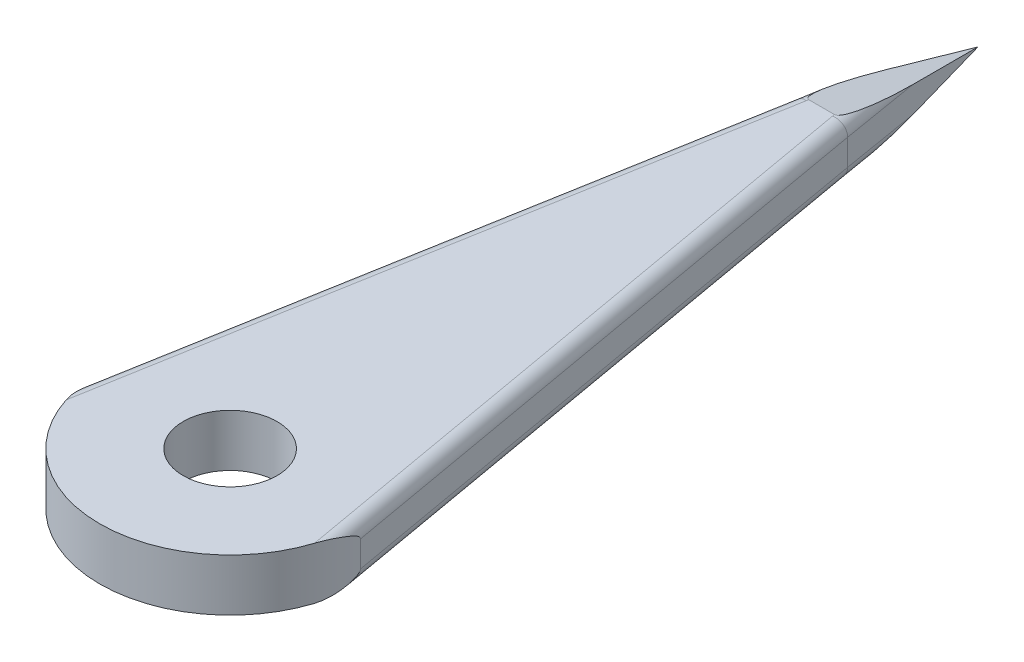
SolidWorks part; units mm, degrees
ref_plane "Front Plane" through (0, 0, 0) normal (0, 0, 1) x (1, 0, 0)
ref_plane "Top Plane" through (0, 0, 0) normal (0, 1, 0) x (1, 0, 0)
ref_plane "Right Plane" through (0, 0, 0) normal (1, 0, 0) x (0, 0, -1)
sketch "Sketch1" plane through (0, 0, 0) normal (0, 1, 0) x (1, 0, 0)
  line L2 (-25, 0) -> (25, 0) construction
  line L3 (25, 0) -> (5, 113.4256)
  line L4 (5, 113.4256) -> (-5, 113.4256)
  line L5 (-5, 113.4256) -> (-25, 0)
  circle A0 centre (0, 0) radius 9
  arc A1 (-25, 0) -> (25, 0) centre (0, 0) ccw
  point P6 (0, 113.4256)
  point P8 (0, -25)
  dimension "D1" = 18
  dimension "D2" = 25
  dimension "D3" = 25
  dimension "D4" = 10
  dimension "D5" = 80
extrude "Boss-Extrude1" add sketch "Sketch1" along normal blind 10
ref_plane "Plane1" through (0, 0, -143.4256) normal (0, 0, -1) x (-1, 0, 0)
sketch "Sketch3" plane through (0, 0, -143.4256) normal (0, 0, -1) x (-1, 0, 0)
  point P0 (0, 5)
sketch "Sketch4" plane through (0, 0, -113.4256) normal (0, 0, -1) x (-1, 0, 0)
  line L1 (-5, 10) -> (5, 10)
  line L2 (-5, 10) -> (-5, 0)
  line L3 (-5, 0) -> (5, 0)
  line L4 (5, 10) -> (5, 0)
loft "Loft2" add profiles "Sketch4", "Sketch3"
fillet "Fillet11" radius 2.5 4 edges at (15, 0, -56.7128) (15, 10, -56.7128) (-15, 0, -56.7128) (-15, 10, -56.7128)
